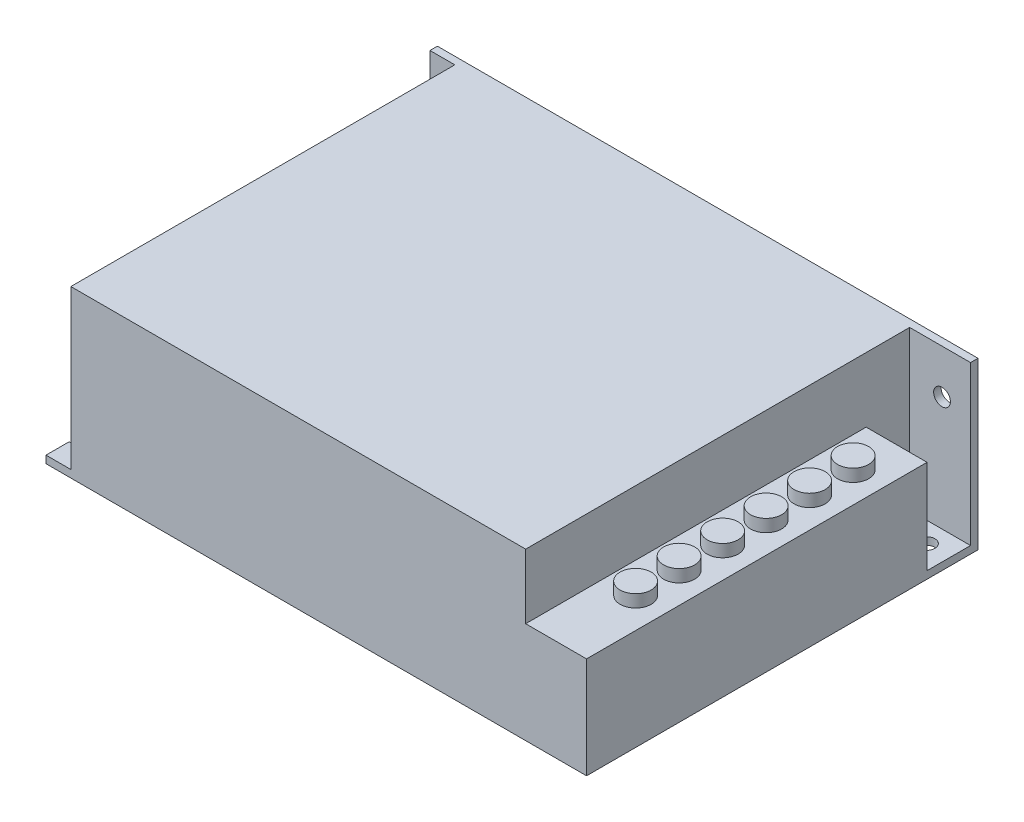
SolidWorks part; units mm, degrees
ref_plane "Front Plane" through (0, 0, 0) normal (0, 0, 1) x (1, 0, 0)
ref_plane "Top Plane" through (0, 0, 0) normal (0, 1, 0) x (1, 0, 0)
ref_plane "Right Plane" through (0, 0, 0) normal (1, 0, 0) x (0, 0, -1)
sketch "Sketch1" plane through (0, 0, 0) normal (0, 1, 0) x (1, 0, 0)
  line L1 (-55.245, 40.005) -> (55.245, 40.005)
  line L2 (-55.245, 40.005) -> (-55.245, -40.005)
  line L3 (-55.245, -40.005) -> (55.245, -40.005)
  line L4 (55.245, 40.005) -> (55.245, -40.005)
  line L5 (-55.245, 40.005) -> (55.245, -40.005) construction
  line L6 (-55.245, -40.005) -> (55.245, 40.005) construction
  point P0 (0, 0)
  dimension "D1" = 110.49
  dimension "D2" = 80.01
extrude "Boss-Extrude1" add sketch "Sketch1" along normal blind 33.909
sketch "Sketch2" plane through (0, 33.909, 0) normal (0, 1, 0) x (1, 0, 0)
  line L3 (-55.245, 40.005) -> (-55.245, -40.005) construction
  line L4 (42.799, 38.481) -> (55.245, 38.481)
  line L5 (42.799, 38.481) -> (42.799, -40.005)
  line L6 (42.799, -40.005) -> (55.245, -40.005)
  line L7 (55.245, 38.481) -> (55.245, -40.005)
  line L8 (55.245, 40.005) -> (-55.245, 40.005) construction
  dimension "D1" = 98.044
  dimension "D2" = 1.524
extrude "Cut-Extrude1" cut sketch "Sketch2" against normal blind 13.208
sketch "Sketch3" plane through (55.245, 0, 0) normal (1, 0, 0) x (0, 0, -1)
  line L0 (40.005, 33.909) -> (40.005, 0) construction
  line L1 (38.481, 20.701) -> (29.591, 20.701)
  line L2 (38.481, 20.701) -> (38.481, 1.524)
  line L3 (38.481, 1.524) -> (29.591, 1.524)
  line L4 (29.591, 20.701) -> (29.591, 1.524)
  line L5 (-40.005, 0) -> (40.005, 0) construction
  dimension "D1" = 10.414
  dimension "D2" = 1.524
extrude "Cut-Extrude2" cut sketch "Sketch3" against normal up to surface (12.446 mm away) up to face at (42.799, 27.305, 0.762)
sketch "Sketch6" plane through (-55.245, 0, 0) normal (-1, 0, 0) x (0, 0, 1)
  line L0 (-40.005, 33.909) -> (40.005, 33.909) construction
  line L1 (-38.481, 33.909) -> (40.005, 33.909)
  line L2 (-38.481, 33.909) -> (-38.481, 13.462)
  line L3 (-38.481, 13.462) -> (29.845, 13.462)
  line L4 (40.005, 33.909) -> (40.005, 1.524)
  line L5 (40.005, 33.909) -> (40.005, 0) construction
  line L6 (-40.005, 0) -> (40.005, 0) construction
  line L7 (-40.005, 33.909) -> (-40.005, 0) construction
  line L8 (29.845, 13.462) -> (29.845, 1.524)
  line L9 (29.845, 1.524) -> (40.005, 1.524)
  dimension "D1" = 1.524
  dimension "D2" = 1.524
  dimension "D3" = 13.462
  dimension "D4" = 10.16
extrude "Cut-Extrude5" cut sketch "Sketch6" against normal blind 5.08
sketch "Sketch4" plane through (0, 0, -40.005) normal (0, 0, -1) x (-1, 0, 0)
  line L0 (-55.245, 33.909) -> (-55.245, 0) construction
  line L1 (-55.245, 33.909) -> (55.245, 33.909) construction
  line L2 (51.816, 26.543) -> (55.245, 26.543)
  line L3 (55.245, 33.909) -> (55.245, 0) construction
  line L4 (51.816, 23.2918) -> (55.245, 23.2918)
  line L5 (55.245, 23.2918) -> (55.245, 26.543)
  circle A0 centre (-49.4157, 24.9047) radius 1.7145
  arc A1 (51.816, 26.543) -> (51.816, 23.2918) centre (51.816, 24.9174) ccw
  dimension "D1" = 3.429
  dimension "D4" = 3.2512
  dimension "D2" = 5.8293
  dimension "D3" = 9.0043
  dimension "D5" = 7.366
  dimension "D6" = 3.429
extrude "Cut-Extrude3" cut sketch "Sketch4" against normal up to next
sketch "Sketch5" plane through (0, 0, 0) normal (0, -1, 0) x (-1, 0, 0)
  line L0 (-55.245, 40.005) -> (55.245, 40.005) construction
  line L1 (-55.245, -40.005) -> (-55.245, 40.005) construction
  line L2 (51.816, -35.2806) -> (55.245, -35.2806)
  line L3 (55.245, 40.005) -> (55.245, -40.005) construction
  line L4 (55.245, -35.2806) -> (55.245, -32.1056)
  line L5 (55.245, -32.1056) -> (51.816, -32.1056)
  line L6 (55.245, -40.005) -> (-55.245, -40.005) construction
  circle A0 centre (-50.3936, 34.3281) radius 1.7145
  arc A1 (51.816, -32.1056) -> (51.816, -35.2806) centre (51.816, -33.6931) ccw
  dimension "D1" = 3.429
  dimension "D4" = 3.175
  dimension "D2" = 5.6769
  dimension "D3" = 4.8514
  dimension "D5" = 4.7244
  dimension "D6" = 3.429
extrude "Cut-Extrude4" cut sketch "Sketch5" against normal through all
sketch "Sketch8" plane through (0, 20.701, 0) normal (0, 1, 0) x (1, 0, 0)
  line L0 (42.799, 29.591) -> (55.245, 29.591) construction
  circle A0 centre (49.022, 20.701) radius 3.175
  point P14 (49.022, 29.591)
  dimension "D1" = 6.35
  dimension "D3" = 8.89
extrude "Boss-Extrude2" add sketch "Sketch8" along normal blind 2.54
pattern_linear "LPattern1" count 6 spacing 8.89 along (0, 0, 1) of "Boss-Extrude2"
hole_wizard "M3 Clearance Hole1" positions "Sketch11" profile "Sketch12" hole size "M3" standard "ANSI Metric"
sketch "Sketch11" plane through (0, 0, 0) normal (0, -1, 0) x (-1, 0, 0)
  circle A0 centre (-50.3936, 34.3281) radius 1.7145 construction
  point P0 (-39.8936, -12.6719)
  point P2 (20.1064, -12.6719)
  dimension "D1" = 47
  dimension "D2" = 60
  dimension "D3" = 10.5
sketch "Sketch12" plane through (39.8936, 0, 12.6719) normal (1, 0, 0) x (0, 0, -1)
  line L0 (0, 0) -> (0, 4.0215)
  line L1 (0, 4.0215) -> (1.7, 3)
  line L2 (1.7, 3) -> (1.7, 0)
  line L5 (1.7, 0) -> (0, 0)
  line L10 (0, 4.0215) -> (-1.7, 3) construction
  line L11 (0, -6.35) -> (0, 107.95) construction
  dimension "Hole Dia." = 3.4
  dimension "Hole Depth" = 3
  dimension "Drill Angle" = 118
